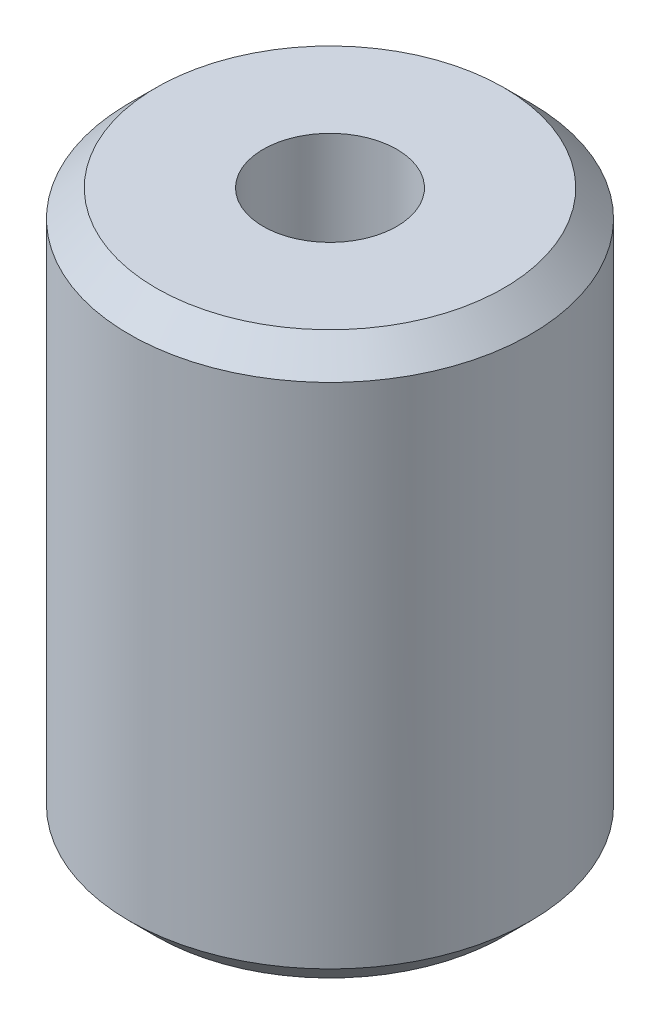
SolidWorks part; units mm, degrees
material "Сталь 3 ГОСТ 535-88"
ref_plane "Спереди" through (0, 0, 0) normal (0, 0, 1) x (1, 0, 0)
ref_plane "Сверху" through (0, 0, 0) normal (0, 1, 0) x (1, 0, 0)
ref_plane "Справа" through (0, 0, 0) normal (1, 0, 0) x (0, 0, -1)
sketch "Эскиз1" plane through (0, 0, 0) normal (0, 1, 0) x (1, 0, 0)
  circle A0 centre (0, 0) radius 7.5
  circle A1 centre (0, 0) radius 2.5
  dimension "D1" = 15
  dimension "D2" = 5
extrude "Бобышка-Вытянуть1" add sketch "Эскиз1" along normal mid plane 21
cosmetic thread "Условное изображение резьбы1" parameters "D1"=6, "D2"=5
chamfer "Фаска1" distance 1 angle 45 2 edges at (0, -10.5, 7.5) (0, 10.5, 7.5)
